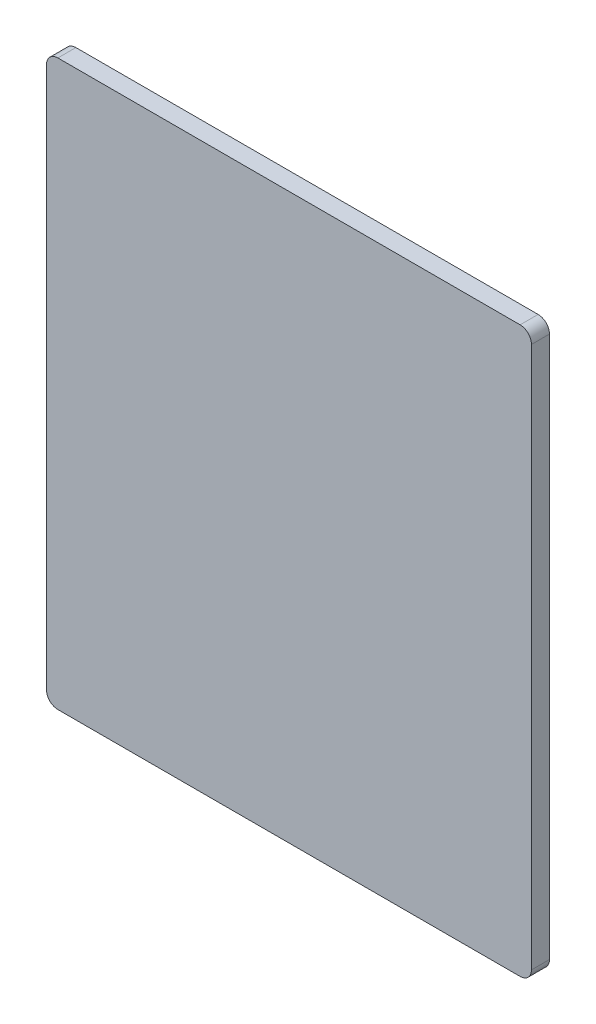
SolidWorks part; units mm, degrees
ref_plane "Front Plane" through (0, 0, 0) normal (0, 0, 1) x (1, 0, 0)
ref_plane "Top Plane" through (0, 0, 0) normal (0, 1, 0) x (1, 0, 0)
ref_plane "Right Plane" through (0, 0, 0) normal (1, 0, 0) x (0, 0, -1)
sketch "Sketch1" plane through (0, 0, 0) normal (0, 0, 1) x (1, 0, 0)
  line L0 (-42.75, -12.7) -> (42.75, -12.7) construction
  line L5 (-40.75, 0) -> (40.75, 0)
  line L6 (-42.75, -2) -> (-42.75, -97.5)
  line L7 (-40.75, -99.5) -> (40.75, -99.5)
  line L8 (42.75, -2) -> (42.75, -97.5)
  line L9 (-42.75, -86.8) -> (42.75, -86.8) construction
  arc A4 (40.75, -99.5) -> (42.75, -97.5) centre (40.75, -97.5) ccw
  arc A5 (-42.75, -97.5) -> (-40.75, -99.5) centre (-40.75, -97.5) ccw
  arc A6 (40.75, 0) -> (42.75, -2) centre (40.75, -2) cw
  arc A7 (-40.75, 0) -> (-42.75, -2) centre (-40.75, -2) ccw
  point P8 (-42.75, -99.5)
  point P11 (42.75, 0)
  point P14 (-42.75, 0)
  dimension "D3" = 2
  dimension "D4" = 12.7
  dimension "D1" = 85.5
  dimension "D2" = 99.5
  dimension "D10" = 12.7
extrude "Boss-Extrude1" add sketch "Sketch1" along normal blind 3.175
